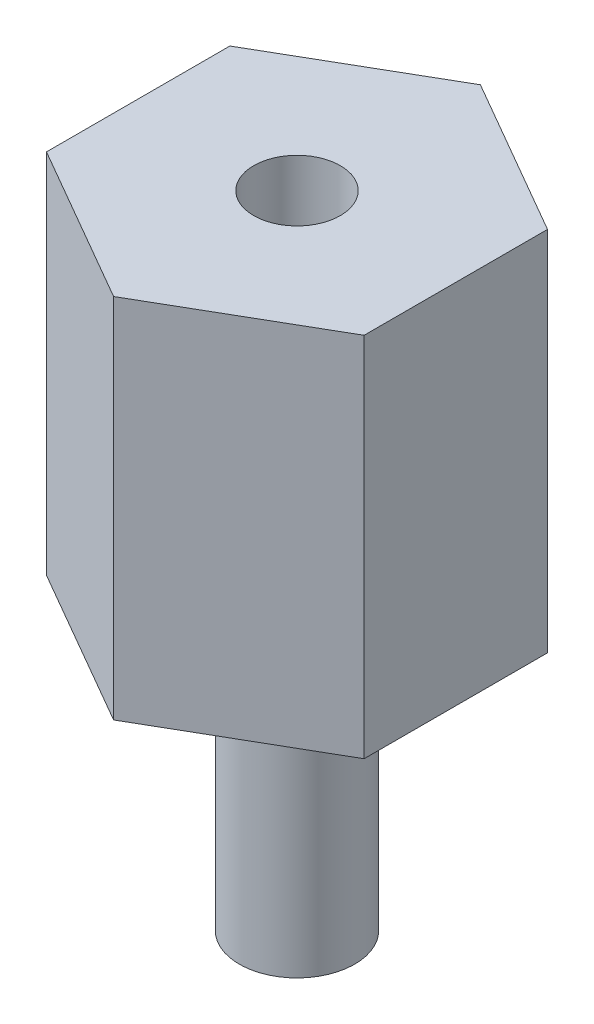
SolidWorks part; units mm, degrees
ref_plane "Front Plane" through (0, 0, 0) normal (0, 0, 1) x (1, 0, 0)
ref_plane "Top Plane" through (0, 0, 0) normal (0, 1, 0) x (1, 0, 0)
ref_plane "Right Plane" through (0, 0, 0) normal (1, 0, 0) x (0, 0, -1)
sketch "Sketch1" plane through (0, 0, 0) normal (0, 1, 0) x (1, 0, 0)
  line L1 (0, 6.3509) -> (-5.5, 3.1754)
  line L2 (-5.5, 3.1754) -> (-5.5, -3.1754)
  line L3 (-5.5, -3.1754) -> (0, -6.3509)
  line L4 (0, -6.3509) -> (5.5, -3.1754)
  line L5 (5.5, -3.1754) -> (5.5, 3.1754)
  line L6 (5.5, 3.1754) -> (0, 6.3509)
  circle A0 centre (0, 0) radius 5.5 construction
  dimension "D1" = 11
extrude "Boss-Extrude1" add sketch "Sketch1" along normal blind 12.7
sketch "Sketch2" plane through (0, 12.7, 0) normal (0, 1, 0) x (1, 0, 0)
  circle A0 centre (0, 0) radius 1.5
  dimension "D1" = 3
extrude "Cut-Extrude1" cut sketch "Sketch2" against normal blind 3.2
sketch "Sketch3" plane through (0, 0, 0) normal (0, -1, 0) x (1, 0, 0)
  circle A0 centre (0, 0) radius 2
  dimension "D1" = 4
extrude "Boss-Extrude2" add sketch "Sketch3" along normal blind 9.5
